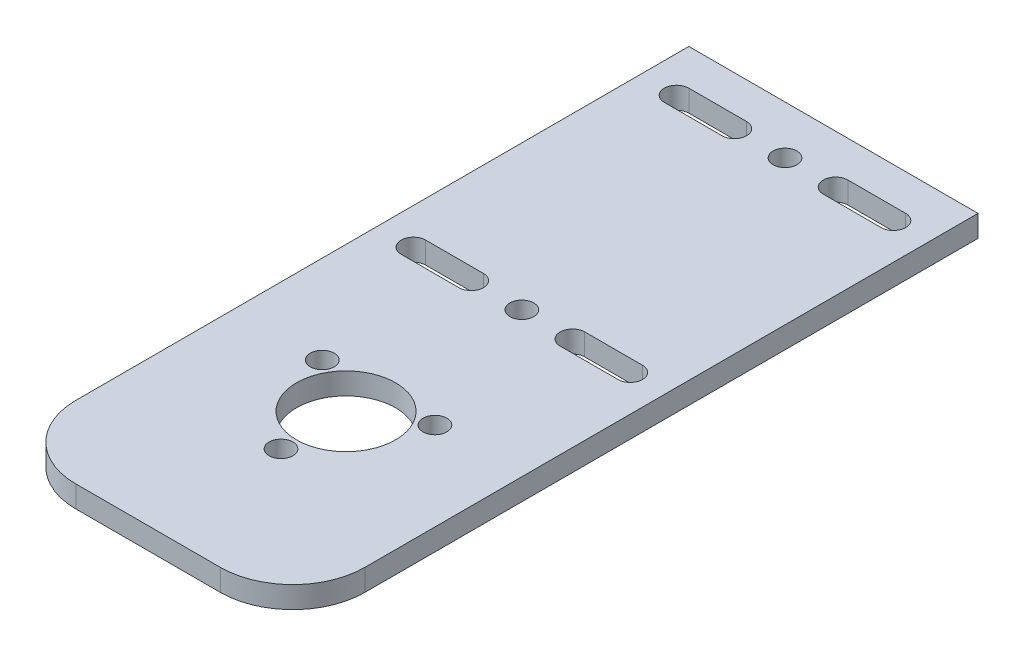
SolidWorks part; units mm, degrees
material "Thornel Mat VMA"
ref_plane "前视基准面" through (0, 0, 0) normal (0, 0, 1) x (1, 0, 0)
ref_plane "上视基准面" through (0, 0, 0) normal (0, 1, 0) x (1, 0, 0)
ref_plane "右视基准面" through (0, 0, 0) normal (1, 0, 0) x (0, 0, -1)
sketch "草图1" plane through (0, 0, 0) normal (0, 1, 0) x (1, 0, 0)
  line L0 (0, 0) -> (0, 50.01)
  line L1 (40, 50.01) -> (40, 0)
  line L9 (0, 50.01) -> (40, 50.01)
  line L10 (0, 10) -> (40, 10) construction
  line L11 (40, 59) -> (0, 59) construction
  line L12 (20, 10) -> (20, 59) construction
  line L13 (0, 0) -> (0, -89.81)
  line L19 (40, -89.81) -> (40, 0)
  line L20 (0, -19.9) -> (40, -19.9) construction
  line L21 (5, -1.7) -> (13, -1.7) construction
  line L22 (5, 0) -> (13, 0)
  line L23 (5, -3.4) -> (13, -3.4)
  line L24 (27, -1.7) -> (35, -1.7) construction
  line L25 (27, 0) -> (35, 0)
  line L26 (27, -3.4) -> (35, -3.4)
  line L28 (40, -98.8) -> (0, -98.8) construction
  line L29 (0, -49.8) -> (40, -49.8) construction
  line L34 (0, -89.81) -> (40, -89.81)
  line L35 (27, -38.1) -> (35, -38.1) construction
  line L36 (27, -39.8) -> (35, -39.8)
  line L37 (27, -36.4) -> (35, -36.4)
  line L38 (5, -38.1) -> (13, -38.1) construction
  line L39 (5, -39.8) -> (13, -39.8)
  line L40 (5, -36.4) -> (13, -36.4)
  line L41 (20, 31.62) -> (12.2058, 18.12) construction
  line L42 (12.2058, 18.12) -> (27.7942, 18.12) construction
  line L43 (27.7942, 18.12) -> (20, 31.62) construction
  arc A4 (5, 0) -> (5, -3.4) centre (5, -1.7) ccw
  arc A5 (13, -3.4) -> (13, 0) centre (13, -1.7) ccw
  arc A6 (27, 0) -> (27, -3.4) centre (27, -1.7) ccw
  arc A7 (35, -3.4) -> (35, 0) centre (35, -1.7) ccw
  circle A8 centre (20, -1.7) radius 1.65
  circle A9 centre (20, -38.1) radius 1.65
  arc A14 (27, -39.8) -> (27, -36.4) centre (27, -38.1) cw
  arc A15 (35, -36.4) -> (35, -39.8) centre (35, -38.1) cw
  arc A16 (5, -39.8) -> (5, -36.4) centre (5, -38.1) cw
  arc A17 (13, -36.4) -> (13, -39.8) centre (13, -38.1) cw
  circle A18 centre (20, 22.62) radius 9 construction
  circle A19 centre (20, 22.62) radius 4.5 construction
  circle A20 centre (20, 31.62) radius 1.65
  circle A21 centre (27.7942, 18.12) radius 1.65
  circle A22 centre (12.2058, 18.12) radius 1.65
  circle A23 centre (27.7942, -57.92) radius 1.65
  circle A24 centre (12.2058, -57.92) radius 1.65
  circle A25 centre (20, -71.42) radius 1.65
  circle A26 centre (20, 22.62) radius 6.85
  circle A27 centre (20, -62.42) radius 6.85
  point P29 (9, -1.7)
  point P34 (31, -1.7)
  point P67 (31, -38.1)
  point P74 (9, -38.1)
  dimension "D5" = 18
  dimension "D8" = 8
  dimension "D9" = 3.3
  dimension "D10" = 13.7
  dimension "D17" = 3.3
  dimension "D2" = 10
  dimension "D3" = 50.01
  dimension "D4" = 40
  dimension "D6" = 8
  dimension "D7" = 49
  dimension "D11" = 27.39
  dimension "D12" = 20
  dimension "D14" = 14
  dimension "D15" = 3.4
  dimension "D16" = 3.4
  dimension "D19" = 33
extrude "凸台-拉伸1" add sketch "草图1" along normal blind 3
fillet "圆角1" radius 10 4 edges at (40, 1.5, 89.81) (0, 1.5, 89.81) (0, 1.5, -50.01) (40, 1.5, -50.01)
sketch "草图2" plane through (0, 3, 0) normal (0, 1, 0) x (1, 0, 0)
  line L0 (0, 5) -> (0, 77.563)
  line L1 (0, 40.01) -> (0, -79.81) construction
  line L2 (0, 77.563) -> (40, 77.563)
  line L3 (40, 77.563) -> (40, 5)
  line L4 (40, -79.81) -> (40, 40.01) construction
  line L5 (40, 5) -> (0, 5)
  line L6 (5, 0) -> (13, 0) construction
  dimension "D1" = 5
extrude "切除-拉伸1" cut sketch "草图2" against normal blind 10
